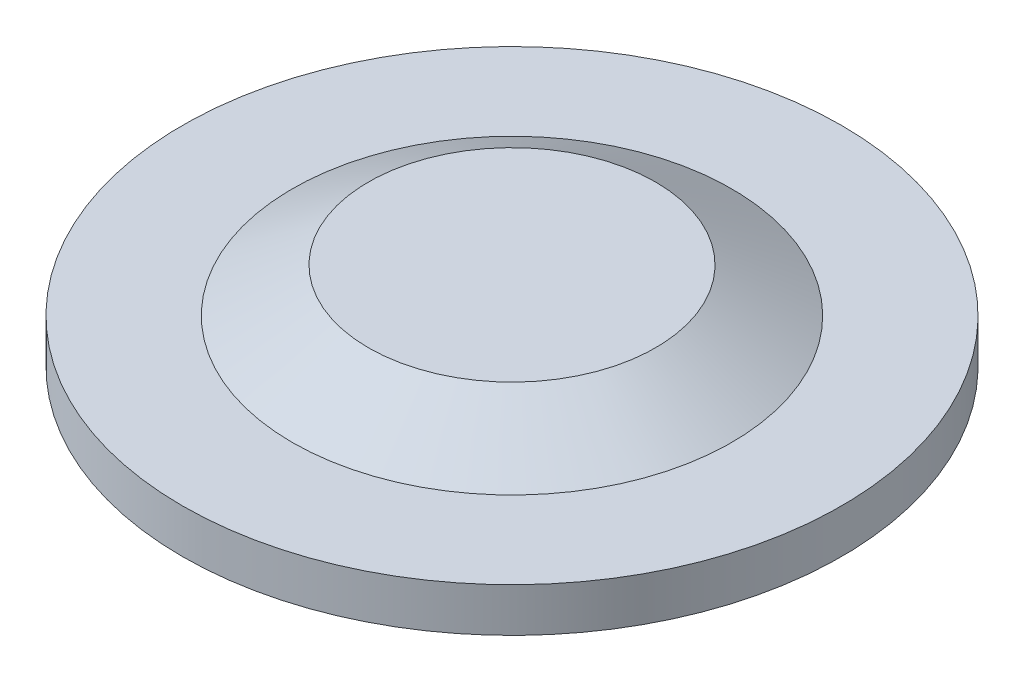
SolidWorks part; units mm, degrees
ref_plane "Front Plane" through (0, 0, 0) normal (0, 0, 1) x (1, 0, 0)
ref_plane "Top Plane" through (0, 0, 0) normal (0, 1, 0) x (1, 0, 0)
ref_plane "Right Plane" through (0, 0, 0) normal (1, 0, 0) x (0, 0, -1)
sketch "Sketch2" plane through (0, 0, 0) normal (0, 1, 0) x (1, 0, 0)
  circle A0 centre (0, 0) radius 5.715
  dimension "D1" = 11.43
extrude "Boss-Extrude1" add sketch "Sketch2" along normal blind 0.762
sketch "Sketch3" plane through (0, 0.762, 0) normal (0, 1, 0) x (1, 0, 0)
  circle A0 centre (0, 0) radius 3.81
  dimension "D1" = 7.62
extrude "Boss-Extrude2" add sketch "Sketch3" along normal blind 0.762 draft 60
